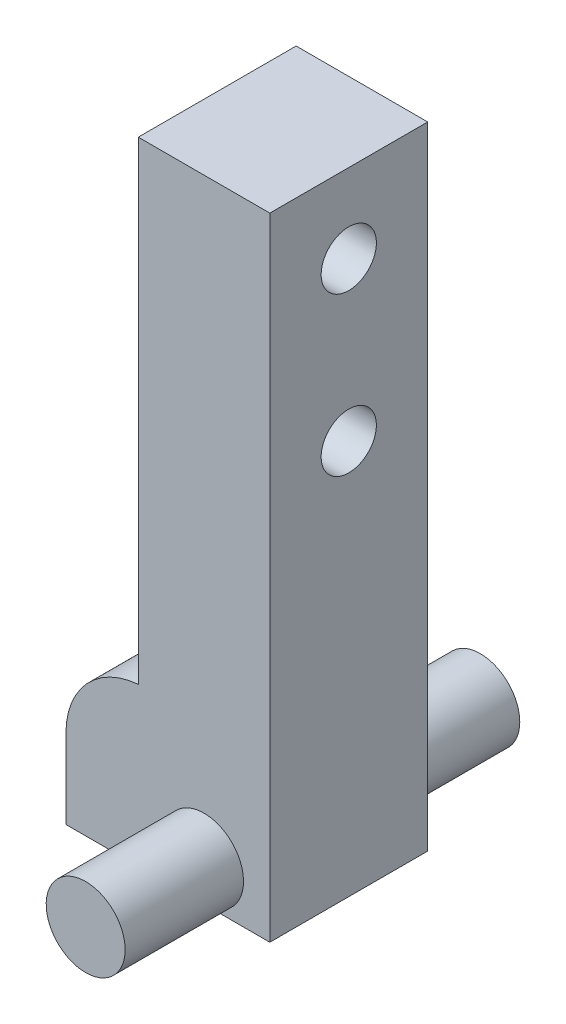
SolidWorks part; units mm, degrees
ref_plane "Top" through (0, 0, 0) normal (0, 0, 1) x (1, 0, 0)
ref_plane "Front" through (0, 0, 0) normal (0, 1, 0) x (1, 0, 0)
ref_plane "Right" through (0, 0, 0) normal (1, 0, 0) x (0, 0, -1)
ref_plane "PivotPinPlane" through (0, 0, 6) normal (0, 0, 1) x (1, 0, 0)
sketch "Sketch3" plane through (0, 0, 0) normal (0, 0, 1) x (1, 0, 0)
  line L0 (-5, 37.3606) -> (-5, -20) construction
  line L1 (-15.5, 0) -> (0, 0)
  line L2 (-10, 48) -> (-10, 11.9791)
  line L3 (-15.5, 6) -> (-15.5, 0)
  line L7 (0, 0) -> (0, 48)
  line L8 (0, 48) -> (-10, 48)
  arc A0 (-15.5, 6) -> (-10, 11.9791) centre (-9.5, 6) cw
  point P18 (-5, 48)
  dimension "R" = 6
  dimension "EDGETOARC" = 4.5
  dimension "HEIGHT" = 48
  dimension "ARCCENTERTOEDGE" = 6
  dimension "DEPTH" = 10
extrude "Base-Extrude" add sketch "Sketch3" along normal blind 12
sketch "Sketch4" plane through (0, 0, 6) normal (0, 0, 1) x (1, 0, 0)
  circle A0 centre (-5, 3) radius 3
  dimension "PINDIAMETER" = 6
  dimension "EDGETOPIN" = 5
  dimension "BOTTOMTOPIN" = 3
extrude "PivotPin" add sketch "Sketch4" along normal mid plane 30
sketch "Sketch5" plane through (-10, 0, 0) normal (-1, 0, 0) x (0, 0, 1)
  line L0 (6, 48) -> (6, -1.4634) construction
  line L1 (12, 48) -> (0, 48) construction
  circle A0 centre (6, 45) radius 1.7
  circle A1 centre (6, 39) radius 1.7
  dimension "DIAMETER" = 3.4
  dimension "TOPTOHOLE" = 3
  dimension "HOLETOHOLE" = 6
extrude "ThroughHoles" [suppressed] cut sketch "Sketch5" against normal through all
sketch "Sketch6" plane through (-10, -53.6761, 53.9968) normal (-1, 0, 0) x (0, 0, 1)
  line L0 (-47.9968, 42.0476) -> (-47.9968, 65.3047) construction
  line L1 (-41.9968, 101.6761) -> (-53.9968, 101.6761) construction
  point P0 (-47.9968, 98.6761)
  dimension "EDGETOTHREAD" = 3
sketch "Sketch7" plane through (-4, 22, 3) normal (0, 1, 0) x (0, 0, 1)
  line L0 (0, 0) -> (0, 7.5022)
  line L1 (0, 7.5022) -> (2.5, 6)
  line L2 (2.5, 6) -> (2.5, 0)
  line L4 (2.5, 0) -> (0, 0)
  line L6 (0, 7.5022) -> (-2.5, 6) construction
  line L7 (0, -4.2442) -> (0, 117.3081) construction
  dimension "Diameter" = 5
  dimension "Depth" = 6
  dimension "Drill Angle" = 118
hole_wizard "M3 x 0.5 #1" positions "Sketch6" profile "Sketch7" legacy
cosmetic thread "Cosmetic Thread1"
sketch "Sketch8" [suppressed] plane through (-4, -47.9368, 54.0596) normal (-1, 0, 0) x (0, 0, 1)
  line L0 (-51.0596, 36.3083) -> (-51.0596, 59.5654) construction
  point P0 (-51.0596, 63.9368)
  dimension "THREADTOTHREAD" = 6
sketch "Sketch9" plane through (-4, 16, 3) normal (0, 1, 0) x (0, 0, 1)
  line L0 (0, 0) -> (0, 7.5022)
  line L1 (0, 7.5022) -> (2.5, 6)
  line L2 (2.5, 6) -> (2.5, 0)
  line L4 (2.5, 0) -> (0, 0)
  line L6 (0, 7.5022) -> (-2.5, 6) construction
  line L7 (0, -4.2442) -> (0, 117.3081) construction
  dimension "Diameter" = 5
  dimension "Depth" = 6
  dimension "Drill Angle" = 118
hole_wizard "M3 x 0.5 #2" positions "Sketch8" profile "Sketch9" legacy
cosmetic thread "Cosmetic Thread2"
sketch "Sketch10" plane through (-10, -45.668, 56.6863) normal (-1, 0, 0) x (0, 0, 1)
  line L0 (-44.6863, 93.668) -> (-56.6863, 93.668) construction
  line L1 (-50.6863, 34.0394) -> (-50.6863, 57.2965) construction
  point P0 (-50.6863, 73.1278)
  dimension "D1" = 20.5402
sketch "Sketch11" plane through (-8, 35, 5) normal (0, 1, 0) x (0, 0, 1)
  line L0 (0, 0) -> (0, 9.5022)
  line L1 (0, 9.5022) -> (2.5, 8)
  line L2 (2.5, 8) -> (2.5, 0)
  line L4 (2.5, 0) -> (0, 0)
  line L6 (0, 9.5022) -> (-2.5, 8) construction
  line L7 (0, -4.2442) -> (0, 117.3081) construction
  dimension "Diameter" = 5
  dimension "Depth" = 8
  dimension "Drill Angle" = 118
hole_wizard "M4 x 0.7 #1" positions "Sketch10" profile "Sketch11" legacy
cosmetic thread "Cosmetic Thread3"
sketch "Sketch12" [suppressed] plane through (-8, -44.5876, 56.6294) normal (-1, 0, 0) x (0, 0, 1)
  line L0 (-51.6294, 32.959) -> (-51.6294, 56.2162) construction
  point P0 (-51.6294, 70.5876)
  dimension "D1" = 14.4598
sketch "Sketch13" plane through (-8, 26, 5) normal (0, 1, 0) x (0, 0, 1)
  line L0 (0, 0) -> (0, 9.5022)
  line L1 (0, 9.5022) -> (2.5, 8)
  line L2 (2.5, 8) -> (2.5, 0)
  line L4 (2.5, 0) -> (0, 0)
  line L6 (0, 9.5022) -> (-2.5, 8) construction
  line L7 (0, -4.2442) -> (0, 117.3081) construction
  dimension "Diameter" = 5
  dimension "Depth" = 8
  dimension "Drill Angle" = 118
hole_wizard "M4 x 0.7 #2" positions "Sketch12" profile "Sketch13" legacy
cosmetic thread "Cosmetic Thread4"
sketch "Sketch14" plane through (-10, -42.7995, 57.7204) normal (-1, 0, 0) x (0, 0, 1)
  line L0 (-51.7204, 31.1709) -> (-51.7204, 54.428) construction
  line L1 (-45.7204, 90.7995) -> (-57.7204, 90.7995) construction
  point P0 (-51.7204, 84.7995)
  dimension "D1" = 6
sketch "Sketch15" plane through (-10, 42, 6) normal (0, 1, 0) x (0, 0, 1)
  line L0 (0, 0) -> (0, 13.2618)
  line L1 (0, 13.2618) -> (2.1, 12)
  line L2 (2.1, 12) -> (2.1, 0)
  line L4 (2.1, 0) -> (0, 0)
  line L6 (0, 13.2618) -> (-2.1, 12) construction
  line L7 (0, -4.2442) -> (0, 117.3081) construction
  dimension "Diameter" = 4.2
  dimension "Depth" = 12
  dimension "Drill Angle" = 118
hole_wizard "M5 x 0.8 #1" positions "Sketch14" profile "Sketch15" legacy
cosmetic thread "Cosmetic Thread5"
sketch "Sketch16" plane through (-10, -44.6417, 57.5839) normal (-1, 0, 0) x (0, 0, 1)
  line L0 (-51.5839, 33.0132) -> (-51.5839, 56.2703) construction
  point P0 (-51.5839, 74.6417)
  dimension "D1" = 12
sketch "Sketch17" plane through (-10, 30, 6) normal (0, 1, 0) x (0, 0, 1)
  line L0 (0, 0) -> (0, 13.2618)
  line L1 (0, 13.2618) -> (2.1, 12)
  line L2 (2.1, 12) -> (2.1, 0)
  line L4 (2.1, 0) -> (0, 0)
  line L6 (0, 13.2618) -> (-2.1, 12) construction
  line L7 (0, -4.2442) -> (0, 117.3081) construction
  dimension "Diameter" = 4.2
  dimension "Depth" = 12
  dimension "Drill Angle" = 118
hole_wizard "M5 Drilled2" positions "Sketch16" profile "Sketch17" legacy
cosmetic thread "Cosmetic Thread6"
sketch "Sketch18" [suppressed] plane through (0, 0, 0) normal (1, 0, 0) x (0, 0, -1)
  point P0 (-3, 22)
ref_plane "Plane1" [suppressed] through (0, 22, 0) normal (0, 1, 0) x (-1, 0, 0)
